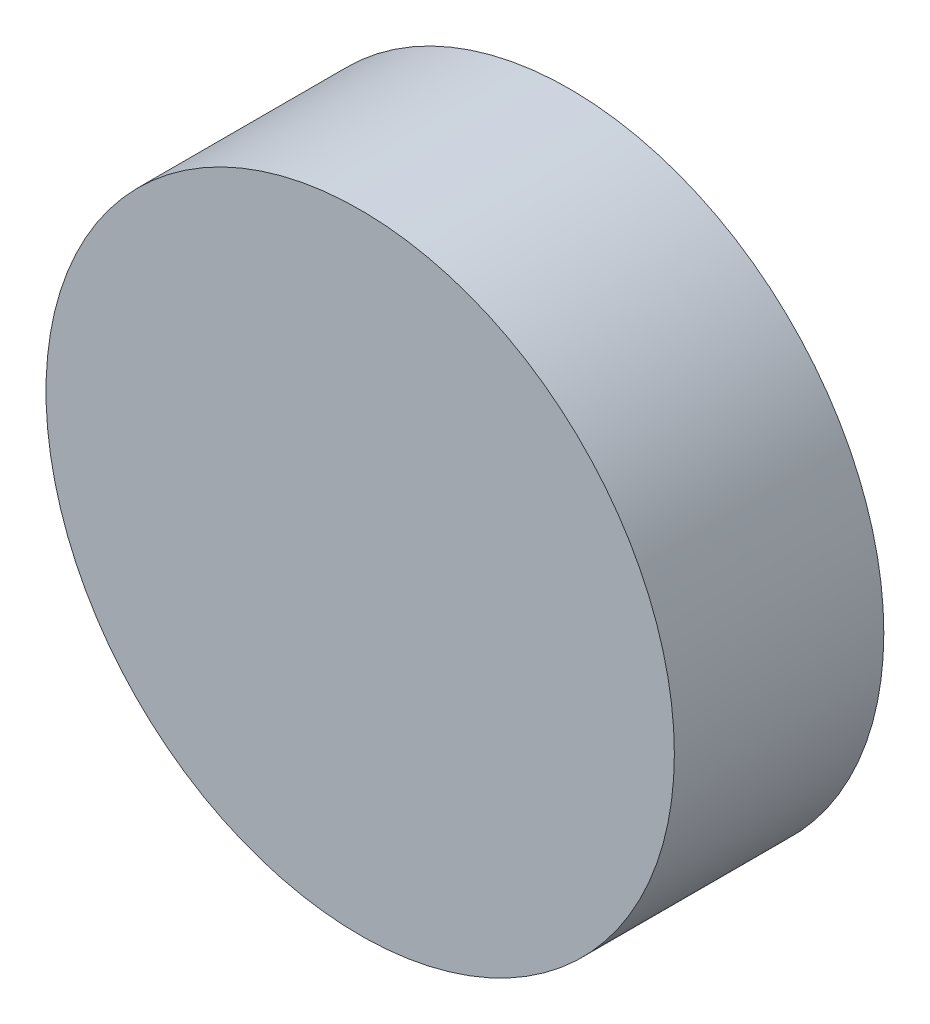
SolidWorks part; units mm, degrees
ref_plane "Front Plane" through (0, 0, 0) normal (1, 0, 0) x (0, 1, 0)
ref_plane "Top Plane" through (0, 0, 0) normal (0, 0, 1) x (0, 1, 0)
ref_plane "Right Plane" through (0, 0, 0) normal (0, 1, 0) x (-1, 0, 0)
sketch "Sketch1" plane through (0, 0, 0) normal (0, 0, 1) x (0, 1, 0)
  circle A0 centre (0, 0) radius 38.1
  dimension "D1" = 76.2
extrude "Boss-Extrude1" add sketch "Sketch1" along normal mid plane 25.4
